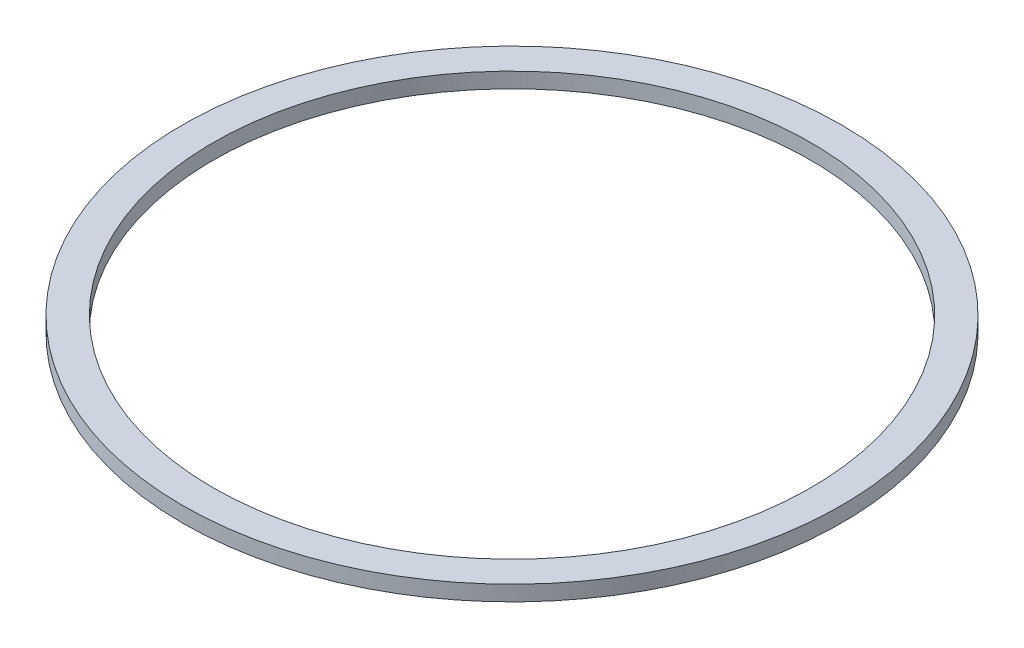
SolidWorks part; units mm, degrees
ref_plane "前视基准面" through (0, 0, 0) normal (0, 0, 1) x (1, 0, 0)
ref_plane "上视基准面" through (0, 0, 0) normal (0, 1, 0) x (1, 0, 0)
ref_plane "右视基准面" through (0, 0, 0) normal (1, 0, 0) x (0, 0, -1)
sketch "草图1" plane through (0, 0, 0) normal (0, 1, 0) x (1, 0, 0)
  circle A0 centre (0, 0) radius 19.5
  circle A1 centre (0, 0) radius 21.5
  circle A2 centre (0, 0) radius 21 construction
  dimension "D1" = 42
  dimension "D2" = 43
  dimension "D3" = 39
extrude "凸台-拉伸1" add sketch "草图1" along normal blind 1
